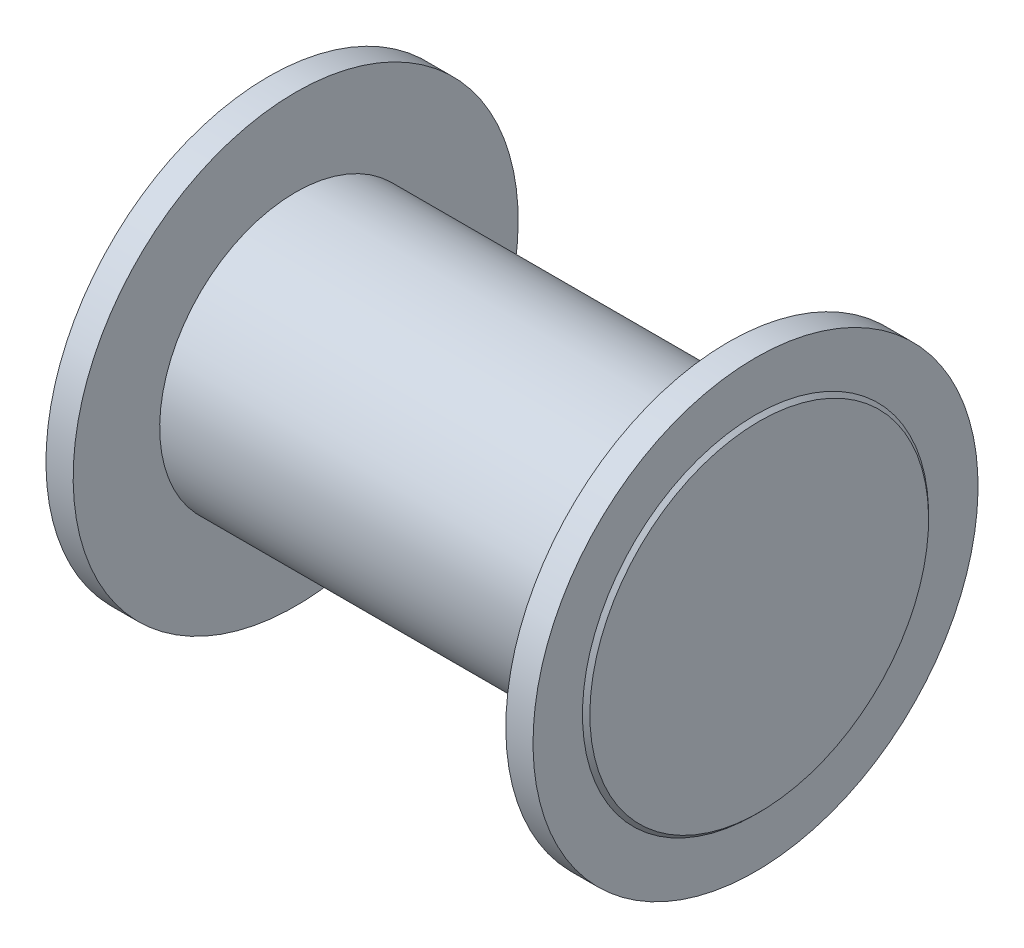
SolidWorks part; units mm, degrees
material "Gray Cast Iron (SN)"
ref_plane "Front Plane" through (0, 0, 0) normal (0, 0, 1) x (1, 0, 0)
ref_plane "Top Plane" through (0, 0, 0) normal (0, 1, 0) x (1, 0, 0)
ref_plane "Right Plane" through (0, 0, 0) normal (1, 0, 0) x (0, 0, -1)
sketch "Sketch1" plane through (0, 0, 0) normal (0, 0, 1) x (1, 0, 0)
  line L0 (200, 0) -> (-200, 0)
  line L1 (-200, 0) -> (-200, 137)
  line L2 (-200, 137) -> (-197, 140)
  line L3 (-197, 140) -> (-197, 180)
  line L4 (-197, 180) -> (-175, 180)
  line L5 (-175, 180) -> (-175, 110)
  line L6 (0, 0) -> (0, 196.4744) construction
  line L7 (200, 0) -> (200, 137)
  line L8 (175, 180) -> (175, 110)
  line L9 (197, 180) -> (175, 180)
  line L10 (197, 140) -> (197, 180)
  line L11 (200, 137) -> (197, 140)
  line L12 (-175, 110) -> (175, 110)
  point P9 (0, 0)
  dimension "D1" = 400
  dimension "D2" = 180
  dimension "D3" = 137
  dimension "D4" = 3
  dimension "D5" = 22
  dimension "D6" = 110
  dimension "D7" = 135
revolve "Revolve1" add sketch "Sketch1" angle 360 about L0
